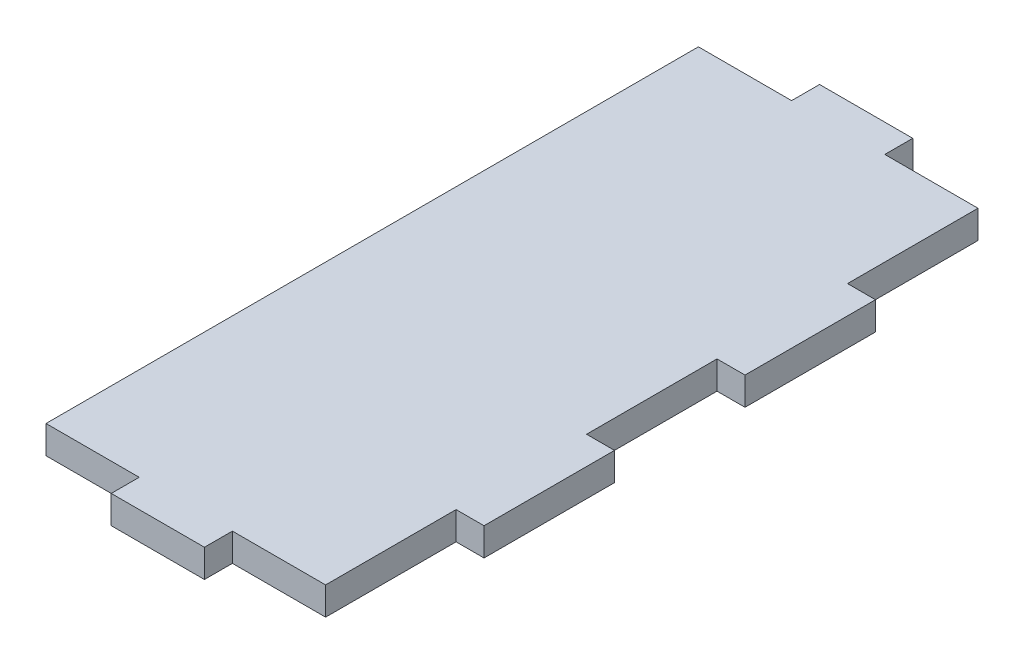
SolidWorks part; units mm, degrees
ref_plane "Front Plane" through (0, 0, 0) normal (0, 0, 1) x (1, 0, 0)
ref_plane "Top Plane" through (0, 0, 0) normal (0, 1, 0) x (1, 0, 0)
ref_plane "Right Plane" through (0, 0, 0) normal (1, 0, 0) x (0, 0, -1)
sketch "Sketch1" plane through (0, 0, 0) normal (0, 1, 0) x (1, 0, 0)
  line L0 (0, 0) -> (10, 0)
  line L1 (10, 0) -> (10, 3)
  line L2 (10, 3) -> (20, 3)
  line L3 (20, 3) -> (20, 0)
  line L4 (20, 0) -> (30, 0)
  line L5 (30, -70) -> (30, -56)
  line L6 (30, -70) -> (20, -70)
  line L7 (20, -70) -> (20, -73)
  line L8 (20, -73) -> (10, -73)
  line L9 (10, -73) -> (10, -70)
  line L10 (10, -70) -> (0, -70)
  line L11 (0, -70) -> (0, 0)
  line L12 (30, -56) -> (33, -56)
  line L13 (33, -56) -> (33, -42)
  line L14 (33, -42) -> (30, -42)
  line L15 (30, -42) -> (30, -28)
  line L16 (30, -28) -> (33, -28)
  line L17 (33, -28) -> (33, -14)
  line L18 (33, -14) -> (30, -14)
  line L19 (30, -14) -> (30, 0)
  dimension "D1" = 10
  dimension "D2" = 10
  dimension "D3" = 10
  dimension "D4" = 3
  dimension "D5" = 70
  dimension "D6" = 70
  dimension "D7" = 3
  dimension "D8" = 10
  dimension "D9" = 10
  dimension "D10" = 14
  dimension "D11" = 14
  dimension "D12" = 14
  dimension "D13" = 14
  dimension "D14" = 3
  dimension "D15" = 3
  dimension "D16" = 3
  dimension "D17" = 3
extrude "Boss-Extrude1" add sketch "Sketch1" along normal blind 3
